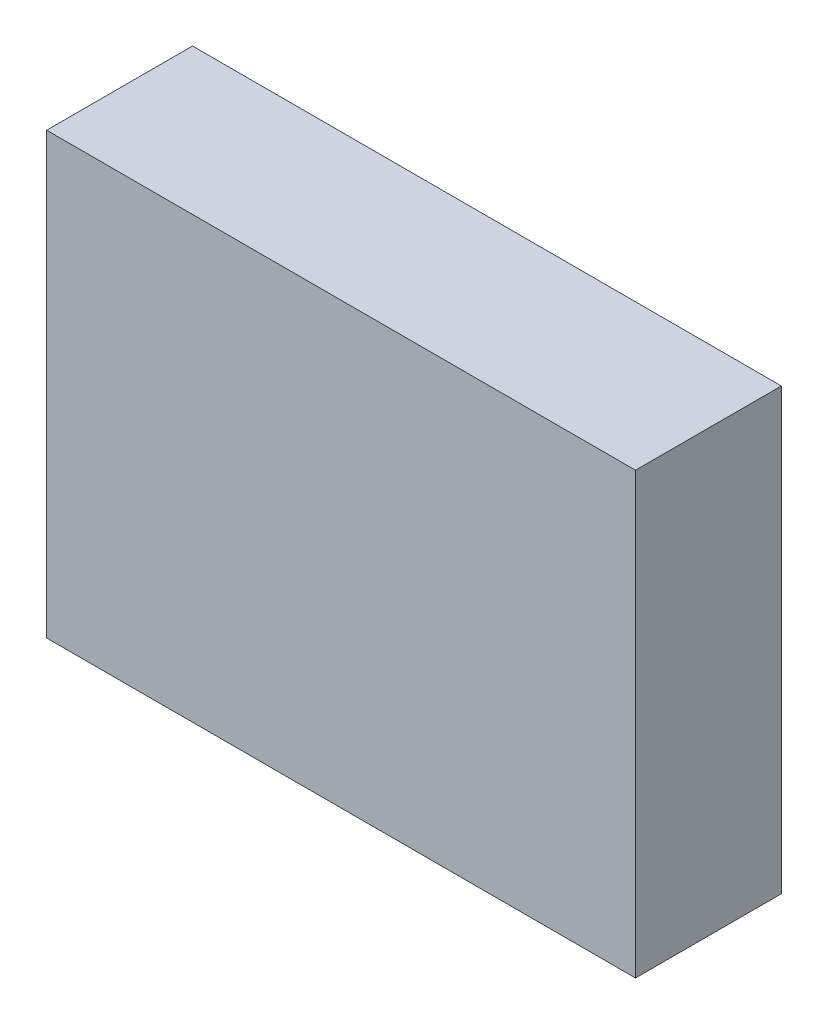
SolidWorks part; units mm, degrees
ref_plane "Plan de face" through (0, 0, 0) normal (0, 0, 1) x (1, 0, 0)
ref_plane "Plan de dessus" through (0, 0, 0) normal (0, 1, 0) x (1, 0, 0)
ref_plane "Plan de droite" through (0, 0, 0) normal (1, 0, 0) x (0, 0, -1)
sketch "Esquisse1" plane through (0, 0, 0) normal (0, 0, 1) x (1, 0, 0)
  line L1 (-30.278, -22.612) -> (30.278, -22.612)
  line L2 (-30.278, -22.612) -> (-30.278, 22.612)
  line L3 (-30.278, 22.612) -> (30.278, 22.612)
  line L4 (30.278, -22.612) -> (30.278, 22.612)
  line L5 (-30.278, -22.612) -> (30.278, 22.612) construction
  line L6 (-30.278, 22.612) -> (30.278, -22.612) construction
  point P0 (0, 0)
extrude "Boss.-Extru.1" add sketch "Esquisse1" along normal blind 15
